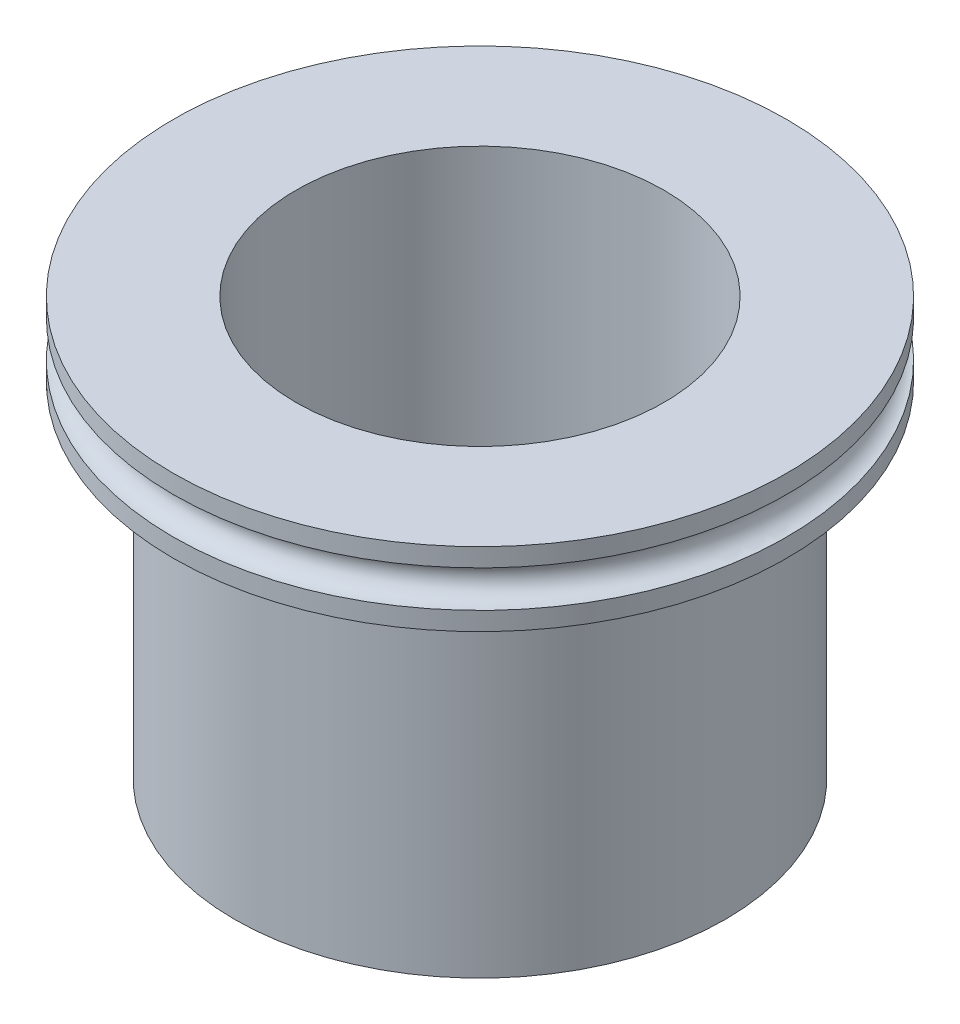
SolidWorks part; units mm, degrees
ref_plane "Alzado" through (0, 0, 0) normal (0, 0, 1) x (1, 0, 0)
ref_plane "Planta" through (0, 0, 0) normal (0, 1, 0) x (1, 0, 0)
ref_plane "Vista lateral" through (0, 0, 0) normal (1, 0, 0) x (0, 0, -1)
sketch "Croquis1" plane through (0, 0, 0) normal (0, 1, 0) x (1, 0, 0)
  circle A0 centre (0, 0) radius 12.5
  dimension "D1" = 25
extrude "Saliente-Extruir1" add sketch "Croquis1" along normal mid plane 3
ref_axis "Eje1" through (0, 1.5, 0) along (0, -1, 0)
sketch "Croquis2" plane through (0, 0, 0) normal (1, 0, 0) x (0, 0, -1)
  line L0 (12.5, -1.5) -> (12.5, 1.5) construction
  circle A0 centre (12.5, 0) radius 0.75
  dimension "D1" = 1.5
revolve "Cortar-Revolución1" cut sketch "Croquis2" angle 360 about axis through (0, 1.5, 0) along (0, -1, 0)
sketch "Croquis4" plane through (0, -1.5, 0) normal (0, -1, 0) x (1, 0, 0)
  circle A0 centre (0, 0) radius 10
  dimension "D1" = 20
extrude "Saliente-Extruir2" add sketch "Croquis4" along normal blind 14
sketch "Croquis3" plane through (0, 1.5, 0) normal (0, 1, 0) x (1, 0, 0)
  circle A0 centre (0, 0) radius 7.5
  dimension "D1" = 15
extrude "Cortar-Extruir1" cut sketch "Croquis3" against normal through all
